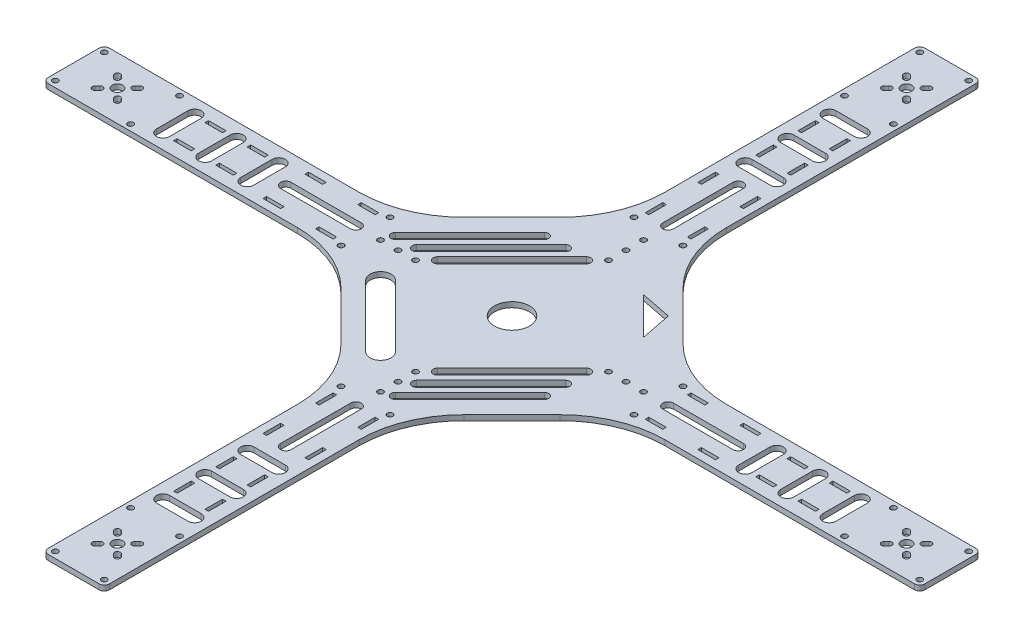
SolidWorks part; units mm, degrees
ref_plane "前视基准面" through (0, 0, 0) normal (0, 0, 1) x (1, 0, 0)
ref_plane "上视基准面" through (0, 0, 0) normal (0, 1, 0) x (1, 0, 0)
ref_plane "右视基准面" through (0, 0, 0) normal (1, 0, 0) x (0, 0, -1)
other "Configuration Table"
sketch "基本底盘" plane through (0, 0, 0) normal (0, 1, 0) x (1, 0, 0)
  line L0 (0, 0) -> (0, -450) construction
  line L1 (4.9497, -4.9497) -> (6.364, -6.364) construction
  line L4 (6.0811, -3.8184) -> (7.4953, -5.2326)
  line L5 (3.8184, -6.0811) -> (5.2326, -7.4953)
  line L6 (-17.5, 25) -> (17.5, 25)
  line L9 (-4.9497, -4.9497) -> (-6.364, -6.364) construction
  line L10 (-3.8184, -6.0811) -> (-5.2326, -7.4953)
  line L11 (-6.0811, -3.8184) -> (-7.4953, -5.2326)
  line L12 (-17.5, 25) -> (-17.5, -25)
  line L15 (-4.9497, 4.9497) -> (-6.364, 6.364) construction
  line L16 (-6.0811, 3.8184) -> (-7.4953, 5.2326)
  line L17 (-3.8184, 6.0811) -> (-5.2326, 7.4953)
  line L18 (17.5, 25) -> (17.5, -25)
  line L21 (4.9497, 4.9497) -> (6.364, 6.364) construction
  line L22 (3.8184, 6.0811) -> (5.2326, 7.4953)
  line L23 (6.0811, 3.8184) -> (7.4953, 5.2326)
  line L24 (0, -25) -> (0, -35)
  line L25 (-9, -35) -> (9, -35) construction
  line L26 (-9, -59) -> (9, -59) construction
  line L27 (-17.5, -25) -> (17.5, -25) construction
  line L28 (-17.5, 25) -> (17.5, -25) construction
  line L29 (17.5, 25) -> (-17.5, -25) construction
  line L30 (-17.5, 25) -> (-13.9645, 21.4645)
  line L31 (-17.5, 0) -> (17.5, 0) construction
  line L36 (-225, -225) -> (225, -225) construction
  line L38 (-13.9645, -21.4645) -> (-13.9645, -95) construction
  line L39 (-17.5, -25) -> (-17.5, -120.1472)
  line L40 (17.5, -25) -> (17.5, -120.1472)
  line L42 (-9, -31.25) -> (9, -31.25)
  line L43 (-9, -38.75) -> (9, -38.75)
  line L44 (-9, -55.25) -> (9, -55.25)
  line L45 (-9, -62.75) -> (9, -62.75)
  line L46 (-9, -83) -> (9, -83) construction
  line L47 (-9, -79.25) -> (9, -79.25)
  line L48 (-9, -86.75) -> (9, -86.75)
  line L49 (9, -38.75) -> (9, -55.25)
  line L50 (7.939, -42) -> (9.939, -42)
  line L51 (7.939, -42) -> (7.939, -52)
  line L52 (9.939, -42) -> (9.939, -52)
  line L53 (7.939, -52) -> (9.939, -52)
  line L54 (7.939, -42) -> (9.939, -52) construction
  line L55 (9.939, -42) -> (7.939, -52) construction
  line L56 (7.939, -66.0412) -> (9.939, -76.0412) construction
  line L57 (9.939, -66.0412) -> (7.939, -76.0412) construction
  line L58 (7.939, -66.0412) -> (9.939, -66.0412)
  line L59 (7.939, -66.0412) -> (7.939, -76.0412)
  line L60 (7.939, -76.0412) -> (9.939, -76.0412)
  line L61 (9.939, -66.0412) -> (9.939, -76.0412)
  line L62 (-7.939, -66.0412) -> (-7.939, -76.0412)
  line L63 (-7.939, -76.0412) -> (-9.939, -76.0412)
  line L64 (-9.939, -66.0412) -> (-9.939, -76.0412)
  line L65 (-7.939, -66.0412) -> (-9.939, -66.0412)
  line L66 (-7.939, -52) -> (-9.939, -52)
  line L67 (-7.939, -42) -> (-7.939, -52)
  line L68 (-7.939, -42) -> (-9.939, -42)
  line L69 (-9.939, -42) -> (-9.939, -52)
  line L90 (0, -136) -> (0, -96) construction
  line L92 (-3, -136) -> (-3, -96)
  line L93 (3, -136) -> (3, -96)
  line L94 (11, -96) -> (13, -96)
  line L95 (13, -96) -> (13, -106)
  line L96 (11, -106) -> (13, -106)
  line L97 (11, -96) -> (11, -106)
  line L98 (-11, -96) -> (-11, -106)
  line L99 (-11, -106) -> (-13, -106)
  line L100 (-13, -96) -> (-13, -106)
  line L101 (-11, -96) -> (-13, -96)
  line L102 (-17.5, -116) -> (17.5, -116) construction
  line L103 (-11, -136) -> (-13, -136)
  line L104 (-13, -136) -> (-13, -126)
  line L105 (-11, -126) -> (-13, -126)
  line L106 (-11, -136) -> (-11, -126)
  line L107 (11, -136) -> (11, -126)
  line L108 (11, -126) -> (13, -126)
  line L109 (13, -136) -> (13, -126)
  line L110 (11, -136) -> (13, -136)
  line L111 (250, -207.5) -> (250, -242.5)
  line L112 (250, -207.5) -> (200, -207.5)
  line L113 (250, -242.5) -> (200, -242.5)
  line L114 (200, -225) -> (190, -225)
  line L115 (250, -207.5) -> (246.4645, -211.0355)
  line L116 (200, -207.5) -> (104.8528, -207.5)
  line L117 (200, -242.5) -> (104.8528, -242.5)
  line L118 (186.25, -234) -> (169.75, -234)
  line L119 (183, -232.939) -> (183, -234.939)
  line L120 (183, -232.939) -> (173, -232.939)
  line L121 (183, -234.939) -> (173, -234.939)
  line L122 (173, -232.939) -> (173, -234.939)
  line L123 (158.9588, -232.939) -> (158.9588, -234.939)
  line L124 (158.9588, -232.939) -> (148.9588, -232.939)
  line L125 (148.9588, -232.939) -> (148.9588, -234.939)
  line L126 (158.9588, -234.939) -> (148.9588, -234.939)
  line L127 (158.9588, -217.061) -> (148.9588, -217.061)
  line L128 (148.9588, -217.061) -> (148.9588, -215.061)
  line L129 (158.9588, -215.061) -> (148.9588, -215.061)
  line L130 (158.9588, -217.061) -> (158.9588, -215.061)
  line L131 (173, -217.061) -> (173, -215.061)
  line L132 (183, -217.061) -> (173, -217.061)
  line L133 (183, -217.061) -> (183, -215.061)
  line L134 (183, -215.061) -> (173, -215.061)
  line L135 (129, -236) -> (129, -238)
  line L136 (129, -238) -> (119, -238)
  line L137 (119, -236) -> (119, -238)
  line L138 (129, -236) -> (119, -236)
  line L139 (129, -214) -> (119, -214)
  line L140 (119, -214) -> (119, -212)
  line L141 (129, -212) -> (119, -212)
  line L142 (129, -214) -> (129, -212)
  line L143 (89, -214) -> (89, -212)
  line L144 (89, -212) -> (99, -212)
  line L145 (99, -214) -> (99, -212)
  line L146 (89, -214) -> (99, -214)
  line L147 (89, -236) -> (99, -236)
  line L148 (99, -236) -> (99, -238)
  line L149 (89, -238) -> (99, -238)
  line L150 (89, -236) -> (89, -238)
  line L151 (200, -207.5) -> (200, -242.5) construction
  line L152 (250, -207.5) -> (200, -242.5) construction
  line L153 (250, -242.5) -> (200, -207.5) construction
  line L154 (225, -207.5) -> (225, -242.5) construction
  line L155 (203.5355, -211.0355) -> (130, -211.0355) construction
  line L156 (183, -232.939) -> (173, -234.939) construction
  line L157 (183, -234.939) -> (173, -232.939) construction
  line L158 (158.9588, -232.939) -> (148.9588, -234.939) construction
  line L159 (158.9588, -234.939) -> (148.9588, -232.939) construction
  line L160 (109, -207.5) -> (109, -242.5) construction
  line L161 (220.0503, -229.9497) -> (218.636, -231.364) construction
  line L162 (221.1816, -231.0811) -> (219.7674, -232.4953)
  line L163 (218.9189, -228.8184) -> (217.5047, -230.2326)
  line L164 (220.0503, -220.0503) -> (218.636, -218.636) construction
  line L165 (218.9189, -221.1816) -> (217.5047, -219.7674)
  line L166 (221.1816, -218.9189) -> (219.7674, -217.5047)
  line L167 (229.9497, -220.0503) -> (231.364, -218.636) construction
  line L168 (228.8184, -218.9189) -> (230.2326, -217.5047)
  line L169 (231.0811, -221.1816) -> (232.4953, -219.7674)
  line L170 (229.9497, -229.9497) -> (231.364, -231.364) construction
  line L171 (231.0811, -228.8184) -> (232.4953, -230.2326)
  line L172 (228.8184, -231.0811) -> (230.2326, -232.4953)
  line L173 (190, -216) -> (190, -234) construction
  line L174 (193.75, -216) -> (193.75, -234)
  line L175 (186.25, -216) -> (186.25, -234)
  line L176 (166, -216) -> (166, -234) construction
  line L177 (169.75, -216) -> (169.75, -234)
  line L178 (162.25, -216) -> (162.25, -234)
  line L179 (142, -216) -> (142, -234) construction
  line L180 (145.75, -216) -> (145.75, -234)
  line L181 (138.25, -216) -> (138.25, -234)
  line L182 (89, -225) -> (129, -225) construction
  line L183 (89, -222) -> (129, -222)
  line L184 (89, -228) -> (129, -228)
  line L185 (17.5, -475) -> (-17.5, -475)
  line L186 (17.5, -475) -> (17.5, -425)
  line L187 (-17.5, -475) -> (-17.5, -425)
  line L188 (0, -425) -> (0, -415)
  line L189 (17.5, -475) -> (13.9645, -471.4645)
  line L190 (17.5, -425) -> (17.5, -329.8528)
  line L191 (-17.5, -425) -> (-17.5, -329.8528)
  line L192 (-9, -411.25) -> (-9, -394.75)
  line L193 (-7.939, -408) -> (-9.939, -408)
  line L194 (-7.939, -408) -> (-7.939, -398)
  line L195 (-9.939, -408) -> (-9.939, -398)
  line L196 (-7.939, -398) -> (-9.939, -398)
  line L197 (-7.939, -383.9588) -> (-9.939, -383.9588)
  line L198 (-7.939, -383.9588) -> (-7.939, -373.9588)
  line L199 (-7.939, -373.9588) -> (-9.939, -373.9588)
  line L200 (-9.939, -383.9588) -> (-9.939, -373.9588)
  line L201 (7.939, -383.9588) -> (7.939, -373.9588)
  line L202 (7.939, -373.9588) -> (9.939, -373.9588)
  line L203 (9.939, -383.9588) -> (9.939, -373.9588)
  line L204 (7.939, -383.9588) -> (9.939, -383.9588)
  line L205 (7.939, -398) -> (9.939, -398)
  line L206 (7.939, -408) -> (7.939, -398)
  line L207 (7.939, -408) -> (9.939, -408)
  line L208 (9.939, -408) -> (9.939, -398)
  line L209 (-11, -354) -> (-13, -354)
  line L210 (-13, -354) -> (-13, -344)
  line L211 (-11, -344) -> (-13, -344)
  line L212 (-11, -354) -> (-11, -344)
  line L213 (11, -354) -> (11, -344)
  line L214 (11, -344) -> (13, -344)
  line L215 (13, -354) -> (13, -344)
  line L216 (11, -354) -> (13, -354)
  line L217 (11, -314) -> (13, -314)
  line L218 (13, -314) -> (13, -324)
  line L219 (11, -324) -> (13, -324)
  line L220 (11, -314) -> (11, -324)
  line L221 (-11, -314) -> (-11, -324)
  line L222 (-11, -324) -> (-13, -324)
  line L223 (-13, -314) -> (-13, -324)
  line L224 (-11, -314) -> (-13, -314)
  line L225 (17.5, -425) -> (-17.5, -425) construction
  line L226 (17.5, -475) -> (-17.5, -425) construction
  line L227 (-17.5, -475) -> (17.5, -425) construction
  line L228 (17.5, -450) -> (-17.5, -450) construction
  line L229 (13.9645, -428.5355) -> (13.9645, -355) construction
  line L230 (-7.939, -408) -> (-9.939, -398) construction
  line L231 (-9.939, -408) -> (-7.939, -398) construction
  line L232 (-7.939, -383.9588) -> (-9.939, -373.9588) construction
  line L233 (-9.939, -383.9588) -> (-7.939, -373.9588) construction
  line L234 (17.5, -334) -> (-17.5, -334) construction
  line L235 (-4.9497, -445.0503) -> (-6.364, -443.636) construction
  line L236 (-6.0811, -446.1816) -> (-7.4953, -444.7674)
  line L237 (-3.8184, -443.9189) -> (-5.2326, -442.5047)
  line L238 (4.9497, -445.0503) -> (6.364, -443.636) construction
  line L239 (3.8184, -443.9189) -> (5.2326, -442.5047)
  line L240 (6.0811, -446.1816) -> (7.4953, -444.7674)
  line L241 (4.9497, -454.9497) -> (6.364, -456.364) construction
  line L242 (6.0811, -453.8184) -> (7.4953, -455.2326)
  line L243 (3.8184, -456.0811) -> (5.2326, -457.4953)
  line L244 (-4.9497, -454.9497) -> (-6.364, -456.364) construction
  line L245 (-3.8184, -456.0811) -> (-5.2326, -457.4953)
  line L246 (-6.0811, -453.8184) -> (-7.4953, -455.2326)
  line L247 (9, -415) -> (-9, -415) construction
  line L248 (9, -418.75) -> (-9, -418.75)
  line L249 (9, -411.25) -> (-9, -411.25)
  line L250 (9, -391) -> (-9, -391) construction
  line L251 (9, -394.75) -> (-9, -394.75)
  line L252 (9, -387.25) -> (-9, -387.25)
  line L253 (9, -367) -> (-9, -367) construction
  line L254 (9, -370.75) -> (-9, -370.75)
  line L255 (9, -363.25) -> (-9, -363.25)
  line L256 (0, -314) -> (0, -354) construction
  line L257 (3, -314) -> (3, -354)
  line L258 (-3, -314) -> (-3, -354)
  line L259 (-250, -242.5) -> (-250, -207.5)
  line L260 (-250, -242.5) -> (-200, -242.5)
  line L261 (-250, -207.5) -> (-200, -207.5)
  line L262 (-200, -225) -> (-190, -225)
  line L263 (-250, -242.5) -> (-246.4645, -238.9645)
  line L264 (-200, -242.5) -> (-104.8528, -242.5)
  line L265 (-200, -207.5) -> (-104.8528, -207.5)
  line L266 (-186.25, -216) -> (-169.75, -216)
  line L267 (-183, -217.061) -> (-183, -215.061)
  line L268 (-183, -217.061) -> (-173, -217.061)
  line L269 (-183, -215.061) -> (-173, -215.061)
  line L270 (-173, -217.061) -> (-173, -215.061)
  line L271 (-158.9588, -217.061) -> (-158.9588, -215.061)
  line L272 (-158.9588, -217.061) -> (-148.9588, -217.061)
  line L273 (-148.9588, -217.061) -> (-148.9588, -215.061)
  line L274 (-158.9588, -215.061) -> (-148.9588, -215.061)
  line L275 (-158.9588, -232.939) -> (-148.9588, -232.939)
  line L276 (-148.9588, -232.939) -> (-148.9588, -234.939)
  line L277 (-158.9588, -234.939) -> (-148.9588, -234.939)
  line L278 (-158.9588, -232.939) -> (-158.9588, -234.939)
  line L279 (-173, -232.939) -> (-173, -234.939)
  line L280 (-183, -232.939) -> (-173, -232.939)
  line L281 (-183, -232.939) -> (-183, -234.939)
  line L282 (-183, -234.939) -> (-173, -234.939)
  line L283 (-129, -214) -> (-129, -212)
  line L284 (-129, -212) -> (-119, -212)
  line L285 (-119, -214) -> (-119, -212)
  line L286 (-129, -214) -> (-119, -214)
  line L287 (-129, -236) -> (-119, -236)
  line L288 (-119, -236) -> (-119, -238)
  line L289 (-129, -238) -> (-119, -238)
  line L290 (-129, -236) -> (-129, -238)
  line L291 (-89, -236) -> (-89, -238)
  line L292 (-89, -238) -> (-99, -238)
  line L293 (-99, -236) -> (-99, -238)
  line L294 (-89, -236) -> (-99, -236)
  line L295 (-89, -214) -> (-99, -214)
  line L296 (-99, -214) -> (-99, -212)
  line L297 (-89, -212) -> (-99, -212)
  line L298 (-89, -214) -> (-89, -212)
  line L299 (-200, -242.5) -> (-200, -207.5) construction
  line L300 (-250, -242.5) -> (-200, -207.5) construction
  line L301 (-250, -207.5) -> (-200, -242.5) construction
  line L302 (-225, -242.5) -> (-225, -207.5) construction
  line L303 (-203.5355, -238.9645) -> (-130, -238.9645) construction
  line L304 (-183, -217.061) -> (-173, -215.061) construction
  line L305 (-183, -215.061) -> (-173, -217.061) construction
  line L306 (-158.9588, -217.061) -> (-148.9588, -215.061) construction
  line L307 (-158.9588, -215.061) -> (-148.9588, -217.061) construction
  line L308 (-109, -242.5) -> (-109, -207.5) construction
  line L309 (-220.0503, -220.0503) -> (-218.636, -218.636) construction
  line L310 (-221.1816, -218.9189) -> (-219.7674, -217.5047)
  line L311 (-218.9189, -221.1816) -> (-217.5047, -219.7674)
  line L312 (-220.0503, -229.9497) -> (-218.636, -231.364) construction
  line L313 (-218.9189, -228.8184) -> (-217.5047, -230.2326)
  line L314 (-221.1816, -231.0811) -> (-219.7674, -232.4953)
  line L315 (-229.9497, -229.9497) -> (-231.364, -231.364) construction
  line L316 (-228.8184, -231.0811) -> (-230.2326, -232.4953)
  line L317 (-231.0811, -228.8184) -> (-232.4953, -230.2326)
  line L318 (-229.9497, -220.0503) -> (-231.364, -218.636) construction
  line L319 (-231.0811, -221.1816) -> (-232.4953, -219.7674)
  line L320 (-228.8184, -218.9189) -> (-230.2326, -217.5047)
  line L321 (-190, -234) -> (-190, -216) construction
  line L322 (-193.75, -234) -> (-193.75, -216)
  line L323 (-186.25, -234) -> (-186.25, -216)
  line L324 (-166, -234) -> (-166, -216) construction
  line L325 (-169.75, -234) -> (-169.75, -216)
  line L326 (-162.25, -234) -> (-162.25, -216)
  line L327 (-142, -234) -> (-142, -216) construction
  line L328 (-145.75, -234) -> (-145.75, -216)
  line L329 (-138.25, -234) -> (-138.25, -216)
  line L330 (-89, -225) -> (-129, -225) construction
  line L331 (-89, -228) -> (-129, -228)
  line L332 (-89, -222) -> (-129, -222)
  line L333 (-35.0736, -162.5736) -> (-62.4264, -189.9264)
  line L334 (35.0736, -162.5736) -> (62.4264, -189.9264)
  line L335 (-62.4264, -260.0736) -> (-35.0736, -287.4264)
  line L336 (62.4264, -260.0736) -> (35.0736, -287.4264)
  circle A0 centre (0, 0) radius 8 construction
  arc A3 (6.0811, -3.8184) -> (3.8184, -6.0811) centre (4.9497, -4.9497) ccw
  arc A4 (5.2326, -7.4953) -> (7.4953, -5.2326) centre (6.364, -6.364) ccw
  arc A7 (-3.8184, -6.0811) -> (-6.0811, -3.8184) centre (-4.9497, -4.9497) ccw
  arc A8 (-7.4953, -5.2326) -> (-5.2326, -7.4953) centre (-6.364, -6.364) ccw
  arc A11 (-6.0811, 3.8184) -> (-3.8184, 6.0811) centre (-4.9497, 4.9497) ccw
  arc A12 (-5.2326, 7.4953) -> (-7.4953, 5.2326) centre (-6.364, 6.364) ccw
  arc A15 (3.8184, 6.0811) -> (6.0811, 3.8184) centre (4.9497, 4.9497) ccw
  arc A16 (7.4953, 5.2326) -> (5.2326, 7.4953) centre (6.364, 6.364) ccw
  circle A17 centre (0, 0) radius 14 construction
  arc A18 (-9, -31.25) -> (-9, -38.75) centre (-9, -35) ccw
  arc A19 (9, -38.75) -> (9, -31.25) centre (9, -35) ccw
  circle A20 centre (0, 0) radius 3
  circle A21 centre (0, 0) radius 88.9 construction
  circle A22 centre (0, 0) radius 64.77 construction
  circle A23 centre (-13.9645, 21.4645) radius 1.6
  circle A24 centre (13.9645, 21.4645) radius 1.6
  circle A25 centre (13.9645, -21.4645) radius 1.6
  circle A26 centre (-13.9645, -21.4645) radius 1.6
  arc A30 (-9, -55.25) -> (-9, -62.75) centre (-9, -59) ccw
  arc A31 (9, -62.75) -> (9, -55.25) centre (9, -59) ccw
  arc A32 (-9, -79.25) -> (-9, -86.75) centre (-9, -83) ccw
  arc A33 (9, -86.75) -> (9, -79.25) centre (9, -83) ccw
  arc A34 (-3, -136) -> (3, -136) centre (0, -136) ccw
  arc A35 (3, -96) -> (-3, -96) centre (0, -96) ccw
  circle A36 centre (225, -225) radius 3
  circle A37 centre (246.4645, -211.0355) radius 1.6
  circle A38 centre (246.4645, -238.9645) radius 1.6
  circle A39 centre (203.5355, -238.9645) radius 1.6
  circle A40 centre (203.5355, -211.0355) radius 1.6
  circle A41 centre (225, -225) radius 8 construction
  circle A42 centre (225, -225) radius 14 construction
  circle A43 centre (225, -225) radius 88.9 construction
  circle A44 centre (225, -225) radius 64.77 construction
  arc A45 (221.1816, -231.0811) -> (218.9189, -228.8184) centre (220.0503, -229.9497) ccw
  arc A46 (217.5047, -230.2326) -> (219.7674, -232.4953) centre (218.636, -231.364) ccw
  arc A47 (218.9189, -221.1816) -> (221.1816, -218.9189) centre (220.0503, -220.0503) ccw
  arc A48 (219.7674, -217.5047) -> (217.5047, -219.7674) centre (218.636, -218.636) ccw
  arc A49 (228.8184, -218.9189) -> (231.0811, -221.1816) centre (229.9497, -220.0503) ccw
  arc A50 (232.4953, -219.7674) -> (230.2326, -217.5047) centre (231.364, -218.636) ccw
  arc A51 (231.0811, -228.8184) -> (228.8184, -231.0811) centre (229.9497, -229.9497) ccw
  arc A52 (230.2326, -232.4953) -> (232.4953, -230.2326) centre (231.364, -231.364) ccw
  arc A53 (193.75, -216) -> (186.25, -216) centre (190, -216) ccw
  arc A54 (186.25, -234) -> (193.75, -234) centre (190, -234) ccw
  arc A55 (169.75, -216) -> (162.25, -216) centre (166, -216) ccw
  arc A56 (162.25, -234) -> (169.75, -234) centre (166, -234) ccw
  arc A57 (145.75, -216) -> (138.25, -216) centre (142, -216) ccw
  arc A58 (138.25, -234) -> (145.75, -234) centre (142, -234) ccw
  arc A59 (89, -222) -> (89, -228) centre (89, -225) ccw
  arc A60 (129, -228) -> (129, -222) centre (129, -225) ccw
  circle A61 centre (0, -450) radius 3
  circle A62 centre (13.9645, -471.4645) radius 1.6
  circle A63 centre (-13.9645, -471.4645) radius 1.6
  circle A64 centre (-13.9645, -428.5355) radius 1.6
  circle A65 centre (13.9645, -428.5355) radius 1.6
  circle A66 centre (0, -450) radius 8 construction
  circle A67 centre (0, -450) radius 14 construction
  circle A68 centre (0, -450) radius 88.9 construction
  circle A69 centre (0, -450) radius 64.77 construction
  arc A70 (-6.0811, -446.1816) -> (-3.8184, -443.9189) centre (-4.9497, -445.0503) ccw
  arc A71 (-5.2326, -442.5047) -> (-7.4953, -444.7674) centre (-6.364, -443.636) ccw
  arc A72 (3.8184, -443.9189) -> (6.0811, -446.1816) centre (4.9497, -445.0503) ccw
  arc A73 (7.4953, -444.7674) -> (5.2326, -442.5047) centre (6.364, -443.636) ccw
  arc A74 (6.0811, -453.8184) -> (3.8184, -456.0811) centre (4.9497, -454.9497) ccw
  arc A75 (5.2326, -457.4953) -> (7.4953, -455.2326) centre (6.364, -456.364) ccw
  arc A76 (-3.8184, -456.0811) -> (-6.0811, -453.8184) centre (-4.9497, -454.9497) ccw
  arc A77 (-7.4953, -455.2326) -> (-5.2326, -457.4953) centre (-6.364, -456.364) ccw
  arc A78 (9, -418.75) -> (9, -411.25) centre (9, -415) ccw
  arc A79 (-9, -411.25) -> (-9, -418.75) centre (-9, -415) ccw
  arc A80 (9, -394.75) -> (9, -387.25) centre (9, -391) ccw
  arc A81 (-9, -387.25) -> (-9, -394.75) centre (-9, -391) ccw
  arc A82 (9, -370.75) -> (9, -363.25) centre (9, -367) ccw
  arc A83 (-9, -363.25) -> (-9, -370.75) centre (-9, -367) ccw
  arc A84 (3, -314) -> (-3, -314) centre (0, -314) ccw
  arc A85 (-3, -354) -> (3, -354) centre (0, -354) ccw
  circle A86 centre (-225, -225) radius 3
  circle A87 centre (-246.4645, -238.9645) radius 1.6
  circle A88 centre (-246.4645, -211.0355) radius 1.6
  circle A89 centre (-203.5355, -211.0355) radius 1.6
  circle A90 centre (-203.5355, -238.9645) radius 1.6
  circle A91 centre (-225, -225) radius 8 construction
  circle A92 centre (-225, -225) radius 14 construction
  circle A93 centre (-225, -225) radius 88.9 construction
  circle A94 centre (-225, -225) radius 64.77 construction
  arc A95 (-221.1816, -218.9189) -> (-218.9189, -221.1816) centre (-220.0503, -220.0503) ccw
  arc A96 (-217.5047, -219.7674) -> (-219.7674, -217.5047) centre (-218.636, -218.636) ccw
  arc A97 (-218.9189, -228.8184) -> (-221.1816, -231.0811) centre (-220.0503, -229.9497) ccw
  arc A98 (-219.7674, -232.4953) -> (-217.5047, -230.2326) centre (-218.636, -231.364) ccw
  arc A99 (-228.8184, -231.0811) -> (-231.0811, -228.8184) centre (-229.9497, -229.9497) ccw
  arc A100 (-232.4953, -230.2326) -> (-230.2326, -232.4953) centre (-231.364, -231.364) ccw
  arc A101 (-231.0811, -221.1816) -> (-228.8184, -218.9189) centre (-229.9497, -220.0503) ccw
  arc A102 (-230.2326, -217.5047) -> (-232.4953, -219.7674) centre (-231.364, -218.636) ccw
  arc A103 (-193.75, -234) -> (-186.25, -234) centre (-190, -234) ccw
  arc A104 (-186.25, -216) -> (-193.75, -216) centre (-190, -216) ccw
  arc A105 (-169.75, -234) -> (-162.25, -234) centre (-166, -234) ccw
  arc A106 (-162.25, -216) -> (-169.75, -216) centre (-166, -216) ccw
  arc A107 (-145.75, -234) -> (-138.25, -234) centre (-142, -234) ccw
  arc A108 (-138.25, -216) -> (-145.75, -216) centre (-142, -216) ccw
  arc A109 (-89, -228) -> (-89, -222) centre (-89, -225) ccw
  arc A110 (-129, -222) -> (-129, -228) centre (-129, -225) ccw
  circle A111 centre (-13.9645, -141.4645) radius 1.6
  circle A112 centre (13.9645, -141.4645) radius 1.6
  circle A113 centre (83.5355, -211.0355) radius 1.6
  circle A114 centre (83.5355, -238.9645) radius 1.6
  circle A115 centre (13.9645, -308.5355) radius 1.6
  circle A116 centre (-13.9645, -308.5355) radius 1.6
  circle A117 centre (-83.5355, -238.9645) radius 1.6
  circle A118 centre (-83.5355, -211.0355) radius 1.6
  arc A119 (104.8528, -242.5) -> (62.4264, -260.0736) centre (104.8528, -302.5) ccw
  arc A120 (104.8528, -207.5) -> (62.4264, -189.9264) centre (104.8528, -147.5) cw
  arc A121 (17.5, -329.8528) -> (35.0736, -287.4264) centre (77.5, -329.8528) cw
  arc A122 (-17.5, -329.8528) -> (-35.0736, -287.4264) centre (-77.5, -329.8528) ccw
  arc A123 (-62.4264, -260.0736) -> (-104.8528, -242.5) centre (-104.8528, -302.5) ccw
  arc A124 (-104.8528, -207.5) -> (-62.4264, -189.9264) centre (-104.8528, -147.5) ccw
  arc A125 (35.0736, -162.5736) -> (17.5, -120.1472) centre (77.5, -120.1472) cw
  arc A126 (-35.0736, -162.5736) -> (-17.5, -120.1472) centre (-77.5, -120.1472) ccw
  point P14 (5.6569, -5.6569)
  point P28 (-5.6569, -5.6569)
  point P34 (0, 0)
  point P42 (-5.6569, 5.6569)
  point P51 (0, -225)
  point P56 (5.6569, 5.6569)
  point P61 (0, 0)
  point P63 (0, 8)
  point P71 (0, -116)
  point P73 (0, -35)
  point P80 (0, -59)
  point P87 (0, -83)
  point P93 (8.939, -47)
  point P95 (8.939, -71.0412)
  point P124 (0, -116)
  point P143 (219.3431, -230.6569)
  point P157 (219.3431, -219.3431)
  point P163 (225, -225)
  point P171 (230.6569, -219.3431)
  point P181 (230.6569, -230.6569)
  point P186 (225, -225)
  point P195 (109, -225)
  point P196 (190, -225)
  point P203 (166, -225)
  point P210 (142, -225)
  point P216 (178, -233.939)
  point P218 (153.9588, -233.939)
  point P242 (109, -225)
  point P265 (-5.6569, -444.3431)
  point P279 (5.6569, -444.3431)
  point P285 (0, -450)
  point P293 (5.6569, -455.6569)
  point P303 (-5.6569, -455.6569)
  point P308 (0, -450)
  point P317 (0, -334)
  point P318 (0, -415)
  point P325 (0, -391)
  point P332 (0, -367)
  point P338 (-8.939, -403)
  point P340 (-8.939, -378.9588)
  point P364 (0, -334)
  point P387 (-219.3431, -219.3431)
  point P401 (-219.3431, -230.6569)
  point P407 (-225, -225)
  point P415 (-230.6569, -230.6569)
  point P425 (-230.6569, -219.3431)
  point P432 (-225, -225)
  point P441 (-109, -225)
  point P442 (-190, -225)
  point P449 (-166, -225)
  point P456 (-142, -225)
  point P462 (-178, -216.061)
  point P464 (-153.9588, -216.061)
  point P488 (-109, -225)
  point P499 (0, -225)
  point P516 (0, -225)
  dimension "D1" = 16
  dimension "D3" = 28
  dimension "D2" = 6
  dimension "D4" = 4
  dimension "D5" = 129.54
  dimension "D9" = 3.2
  dimension "D11" = 4
  dimension "D12" = 60
  dimension "D14" = 10
  dimension "D15" = 3
  dimension "D10" = 2
  dimension "D6" = 35
  dimension "D7" = 50
  dimension "D8" = 5
  dimension "D16" = 2
  dimension "D17" = 10
  dimension "D18" = 2
sketch "草图1" plane through (0, 0, 0) normal (0, 1, 0) x (1, 0, 0)
  line L0 (14.1421, -175.5025) -> (49.4975, -210.8579) construction
  line L1 (14.1421, -175.5025) -> (-49.4975, -239.1421) construction
  line L2 (49.4975, -210.8579) -> (-14.1421, -274.4975) construction
  line L3 (-49.4975, -239.1421) -> (-14.1421, -274.4975) construction
  line L4 (14.1421, -175.5025) -> (-14.1421, -274.4975) construction
  line L5 (49.4975, -210.8579) -> (-49.4975, -239.1421) construction
  line L6 (0, 0) -> (0, -450) construction
  line L7 (-48.7132, -218.7132) -> (-6.2868, -176.2868) construction
  line L8 (37.4767, -187.5233) -> (44.5477, -180.4523)
  line L9 (0, -170) -> (-55, -225) construction
  line L10 (-55, -225) -> (-65, -225)
  line L11 (-65, -225) -> (0, -160) construction
  line L12 (-75, -225) -> (0, -150) construction
  line L13 (-60.7132, -218.7132) -> (-18.2868, -176.2868) construction
  line L14 (-50.481, -216.9454) -> (-8.0546, -174.519)
  line L15 (-46.9454, -220.481) -> (-4.519, -178.0546)
  line L16 (-62.481, -216.9454) -> (-20.0546, -174.519)
  line L17 (-58.9454, -220.481) -> (-16.519, -178.0546)
  line L18 (-72.7132, -218.7132) -> (-30.2868, -176.2868) construction
  line L19 (-74.481, -216.9454) -> (-32.0546, -174.519)
  line L20 (-70.9454, -220.481) -> (-28.519, -178.0546)
  line L21 (0, -225) -> (31.8198, -193.1802) construction
  line L22 (6.2868, -273.7132) -> (48.7132, -231.2868) construction
  line L23 (8.0546, -275.481) -> (50.481, -233.0546)
  line L24 (4.519, -271.9454) -> (46.9454, -229.519)
  line L25 (6.2868, -285.7132) -> (48.7132, -243.2868) construction
  line L26 (8.0546, -287.481) -> (50.481, -245.0546)
  line L27 (4.519, -283.9454) -> (46.9454, -241.519)
  line L28 (6.2868, -297.7132) -> (48.7132, -255.2868) construction
  line L29 (8.0546, -299.481) -> (50.481, -257.0546)
  line L30 (4.519, -295.9454) -> (46.9454, -253.519)
  line L31 (-31.8198, -256.8198) -> (-37.4767, -262.4767)
  line L32 (44.5477, -180.4523) -> (48.0833, -198.1299)
  line L33 (-55.1543, -244.799) -> (-19.799, -280.1543) construction
  line L34 (31.8198, -193.1802) -> (37.4767, -187.5233)
  line L37 (-50.9117, -240.5563) -> (-15.5563, -275.9117)
  line L38 (-59.397, -249.0416) -> (-24.0416, -284.397)
  line L39 (26.8701, -176.9167) -> (48.0833, -198.1299)
  line L40 (26.8701, -176.9167) -> (44.5477, -180.4523)
  circle A0 centre (0, -225) radius 75 construction
  circle A1 centre (0, -225) radius 65 construction
  circle A2 centre (0, -225) radius 55 construction
  circle A3 centre (0, -150) radius 1.6
  circle A4 centre (0, -160) radius 1.6
  circle A5 centre (0, -170) radius 1.6
  circle A6 centre (75, -225) radius 1.6
  circle A7 centre (65, -225) radius 1.6
  circle A8 centre (55, -225) radius 1.6
  circle A9 centre (0, -300) radius 1.6
  circle A10 centre (0, -290) radius 1.6
  circle A11 centre (0, -280) radius 1.6
  circle A12 centre (-75, -225) radius 1.6
  circle A13 centre (-65, -225) radius 1.6
  circle A14 centre (-55, -225) radius 1.6
  arc A15 (-50.481, -216.9454) -> (-46.9454, -220.481) centre (-48.7132, -218.7132) ccw
  arc A16 (-4.519, -178.0546) -> (-8.0546, -174.519) centre (-6.2868, -176.2868) ccw
  arc A17 (-62.481, -216.9454) -> (-58.9454, -220.481) centre (-60.7132, -218.7132) ccw
  arc A18 (-16.519, -178.0546) -> (-20.0546, -174.519) centre (-18.2868, -176.2868) ccw
  arc A19 (-74.481, -216.9454) -> (-70.9454, -220.481) centre (-72.7132, -218.7132) ccw
  arc A20 (-28.519, -178.0546) -> (-32.0546, -174.519) centre (-30.2868, -176.2868) ccw
  arc A21 (8.0546, -275.481) -> (4.519, -271.9454) centre (6.2868, -273.7132) cw
  arc A22 (46.9454, -229.519) -> (50.481, -233.0546) centre (48.7132, -231.2868) cw
  arc A23 (8.0546, -287.481) -> (4.519, -283.9454) centre (6.2868, -285.7132) cw
  arc A24 (46.9454, -241.519) -> (50.481, -245.0546) centre (48.7132, -243.2868) cw
  arc A25 (8.0546, -299.481) -> (4.519, -295.9454) centre (6.2868, -297.7132) cw
  arc A26 (46.9454, -253.519) -> (50.481, -257.0546) centre (48.7132, -255.2868) cw
  arc A29 (-50.9117, -240.5563) -> (-59.397, -249.0416) centre (-55.1543, -244.799) ccw
  arc A30 (-24.0416, -284.397) -> (-15.5563, -275.9117) centre (-19.799, -280.1543) ccw
  circle A31 centre (0, -225) radius 10
  point P1 (0, -225)
  point P38 (0, -225)
  point P40 (-27.5, -197.5)
  point P47 (-39.5, -197.5)
  point P54 (-51.5, -197.5)
  point P60 (27.5, -252.5)
  point P67 (27.5, -264.5)
  point P74 (27.5, -276.5)
  point P85 (-37.4767, -262.4767)
  point P92 (37.4767, -187.5233)
  dimension "D3" = 3.2
  dimension "D4" = 3.2
  dimension "D5" = 3.2
  dimension "D7" = 3
  dimension "D8" = 8
  dimension "D9" = 8
  dimension "D12" = 20
  dimension "D1" = 50
  dimension "D2" = 90
  dimension "D10" = 15
  dimension "D11" = 10
  dimension "D6" = 4
extrude "凸台-拉伸1" add sketch "基本底盘" along normal blind 3
extrude "切除-拉伸1" cut sketch "草图1" along normal through all
fillet "圆角1" radius 3 8 edges at (-250, 1.5, 242.5) (-250, 1.5, 207.5) (-17.5, 1.5, -25) (17.5, 1.5, -25) (250, 1.5, 207.5) (250, 1.5, 242.5) (-17.5, 1.5, 475) (17.5, 1.5, 475)
